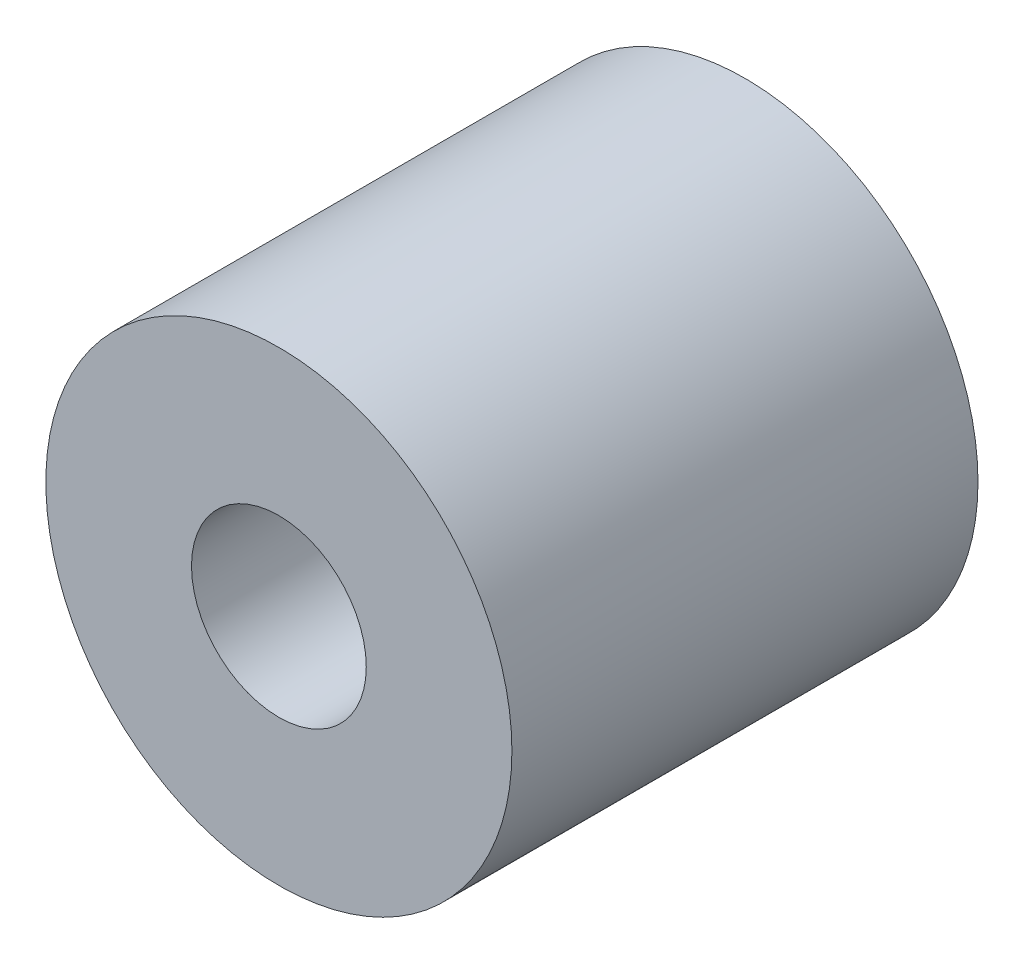
SolidWorks part; units mm, degrees
material "ABS"
ref_plane "Front" through (0, 0, 0) normal (0, 0, 1) x (1, 0, 0)
ref_plane "Top" through (0, 0, 0) normal (0, 1, 0) x (1, 0, 0)
ref_plane "Right" through (0, 0, 0) normal (1, 0, 0) x (0, 0, -1)
sketch "草图1" plane through (0, 0, 0) normal (0, 0, 1) x (1, 0, 0)
  circle A0 centre (0, 0) radius 4
  circle A1 centre (0, 0) radius 1.5
  dimension "D1" = 3
  dimension "D2" = 8
extrude "凸台-拉伸1" add sketch "草图1" along normal blind 8
